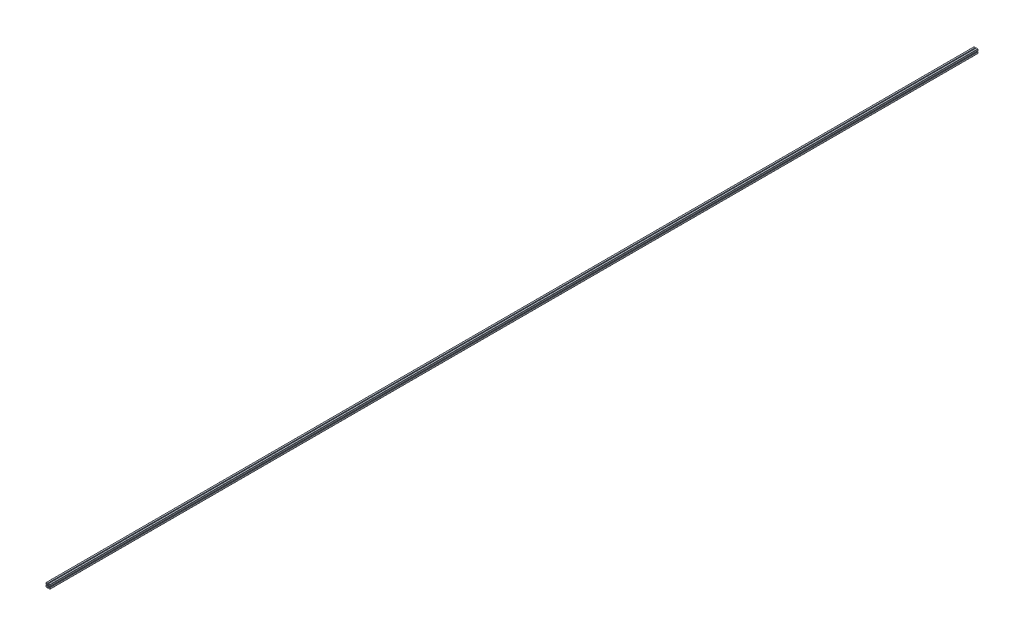
SolidWorks part; units mm, degrees
ref_plane "Front" through (0, 0, 0) normal (0, 0, 1) x (1, 0, 0)
ref_plane "Top" through (0, 0, 0) normal (0, 1, 0) x (1, 0, 0)
ref_plane "Right" through (0, 0, 0) normal (1, 0, 0) x (0, 0, -1)
sketch "草图1" plane through (0, 0, 0) normal (0, 0, 1) x (1, 0, 0)
  line L1 (-20, 20) -> (20, 20)
  line L2 (-20, 20) -> (-20, -20)
  line L3 (-20, -20) -> (20, -20)
  line L4 (20, 20) -> (20, -20)
  line L5 (-20, 20) -> (20, -20) construction
  line L6 (-20, -20) -> (20, 20) construction
  point P0 (0, 0)
  dimension "D1" = 40
extrude "凸台-拉伸1" add sketch "草图1" along normal up to vertex (9282.5 mm away)
sketch "草图2" plane through (0, 0, 9282.5) normal (0, 0, 1) x (1, 0, 0)
  circle A0 centre (0, 0) radius 4.05
  dimension "D1" = 8.1
extrude "切除-拉伸1" cut sketch "草图2" against normal blind 10000
sketch "草图4" plane through (0, 0, 9282.5) normal (0, 0, 1) x (1, 0, 0)
  line L0 (20, -20) -> (20, 20) construction
  line L1 (20, 0) -> (20, 4)
  line L2 (20, 0) -> (20, -2.652)
  line L3 (7.8769, 2.6) -> (7.8769, -2.6)
  line L4 (20, 4) -> (16, 4)
  line L5 (20, -2.652) -> (16, -2.652)
  line L6 (16, 10.5) -> (16, 4)
  line L7 (16, 10.5) -> (7.8769, 2.6)
  line L8 (16, -10.5) -> (7.8769, -2.6)
  line L9 (16, -2.652) -> (16, -10.5)
  point P11 (7.8769, 0)
  point P12 (16, 0)
extrude "切除-拉伸2" cut sketch "草图4" against normal blind 10000
fillet "圆角1" radius 1 8 edges at (16, 10.5, 4641.25) (16, -10.5, 4641.25) (7.8769, 2.6, 4641.25) (20, -2.652, 4641.25) (16, -2.652, 4641.25) (20, 4, 4641.25) (16, 4, 4641.25) (7.8769, -2.6, 4641.25)
pattern_circular "阵列(圆周)2" count 4 over 360 about axis through (0, 0, 0) along (0, 0, 1) of "切除-拉伸2"
fillet "圆角2" radius 1 8 edges at (10.5, 16, 4641.25) (-10.5, 16, 4641.25) (-4, 20, 4641.25) (2.652, 16, 4641.25) (2.652, 20, 4641.25) (-2.6, 7.8769, 4641.25) (-4, 16, 4641.25) (2.6, 7.8769, 4641.25)
fillet "圆角3" radius 1 8 edges at (-7.8769, -2.6, 4641.25) (-7.8769, 2.6, 4641.25) (-20, 2.652, 4641.25) (-16, 10.5, 4641.25) (-20, -4, 4641.25) (-16, -4, 4641.25) (-16, -10.5, 4641.25) (-16, 2.652, 4641.25)
fillet "圆角4" radius 1 8 edges at (4, -20, 4641.25) (4, -16, 4641.25) (10.5, -16, 4641.25) (-2.652, -20, 4641.25) (2.6, -7.8769, 4641.25) (-2.6, -7.8769, 4641.25) (-2.652, -16, 4641.25) (-10.5, -16, 4641.25)
fillet "圆角5" radius 2 4 edges at (-20, -20, 4641.25) (20, -20, 4641.25) (-20, 20, 4641.25) (20, 20, 4641.25)
